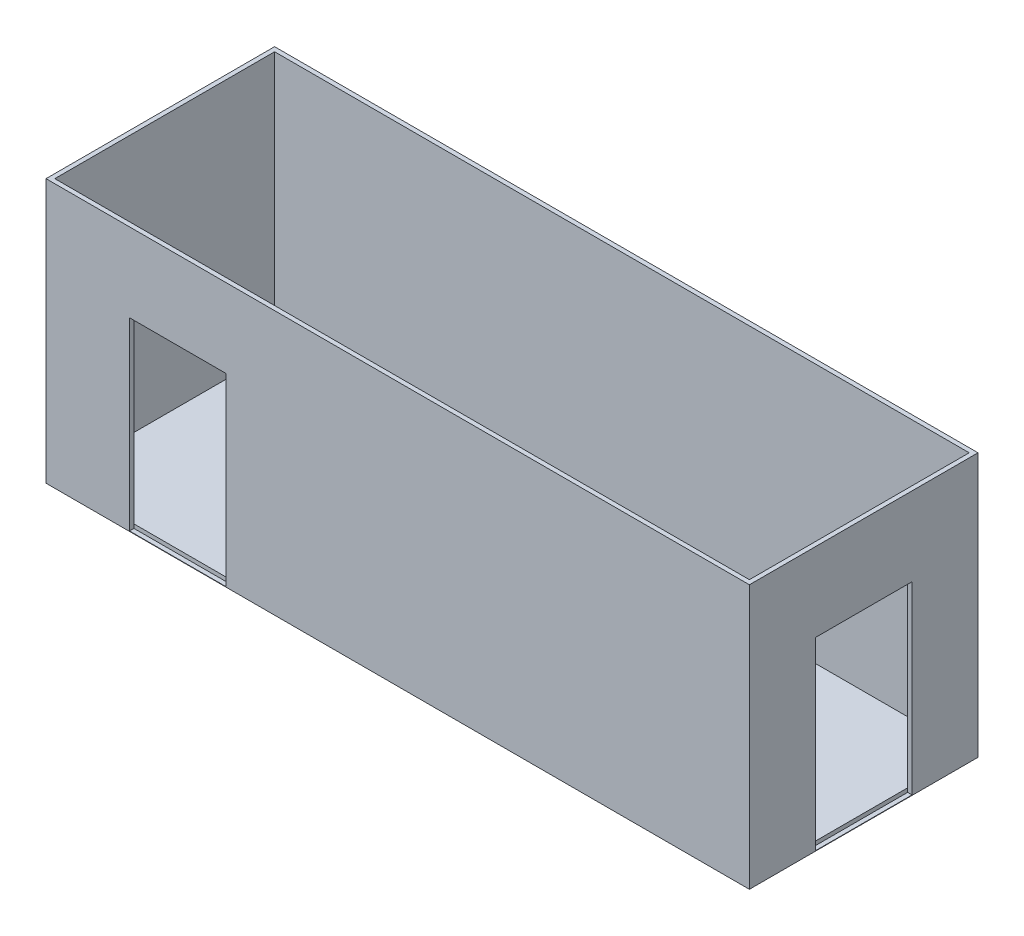
SolidWorks part; units mm, degrees
ref_plane "Front Plane" through (0, 0, 0) normal (0, 0, 1) x (1, 0, 0)
ref_plane "Top Plane" through (0, 0, 0) normal (0, 1, 0) x (1, 0, 0)
ref_plane "Right Plane" through (0, 0, 0) normal (1, 0, 0) x (0, 0, -1)
sketch "Sketch2" plane through (0, 0, 0) normal (0, 1, 0) x (1, 0, 0)
  line L1 (4000, -1300) -> (-4000, -1300)
  line L2 (4000, -1300) -> (4000, 1300)
  line L3 (4000, 1300) -> (-4000, 1300)
  line L4 (-4000, -1300) -> (-4000, 1300)
  line L5 (4000, -1300) -> (-4000, 1300) construction
  line L6 (4000, 1300) -> (-4000, -1300) construction
  point P0 (0, 0)
  dimension "D1" = 8000
  dimension "D2" = 2600
extrude "Boss-Extrude1" add sketch "Sketch2" along normal blind 3000
shell "Shell1" thickness 50
sketch "Sketch3" plane through (0, 0, 1300) normal (0, 0, 1) x (1, 0, 0)
  line L0 (-4000, 3000) -> (-4000, 0) construction
  line L1 (-3050, 2105) -> (-1950, 2105)
  line L2 (-3050, 2105) -> (-3050, 5)
  line L3 (-3050, 5) -> (-1950, 5)
  line L4 (-1950, 2105) -> (-1950, 5)
  line L5 (-3050, 2105) -> (-1950, 5) construction
  line L6 (-3050, 5) -> (-1950, 2105) construction
  line L7 (-4000, 0) -> (4000, 0) construction
  point P4 (-2500, 1055)
  dimension "D1" = 950
  dimension "D2" = 2100
  dimension "D3" = 2105
  dimension "D4" = 1100
extrude "Cut-Extrude1" cut sketch "Sketch3" against normal blind 50
sketch "Sketch4" plane through (4000, 0, 0) normal (1, 0, 0) x (0, 0, -1)
  line L0 (0, -123.5539) -> (0, 3111.1761) construction
  line L1 (-550, 2105) -> (550, 2105)
  line L2 (-550, 2105) -> (-550, 5)
  line L3 (-550, 5) -> (550, 5)
  line L4 (550, 2105) -> (550, 5)
  line L5 (-550, 2105) -> (550, 5) construction
  line L6 (-550, 5) -> (550, 2105) construction
  line L7 (-1300, 0) -> (1300, 0) construction
  point P4 (0, 1055)
  point P8 (90.7705, 1456.6777)
  point P9 (0, 1448.4259)
  dimension "D1" = 1100
  dimension "D2" = 2100
  dimension "D3" = 2105
extrude "Cut-Extrude2" cut sketch "Sketch4" against normal blind 50
